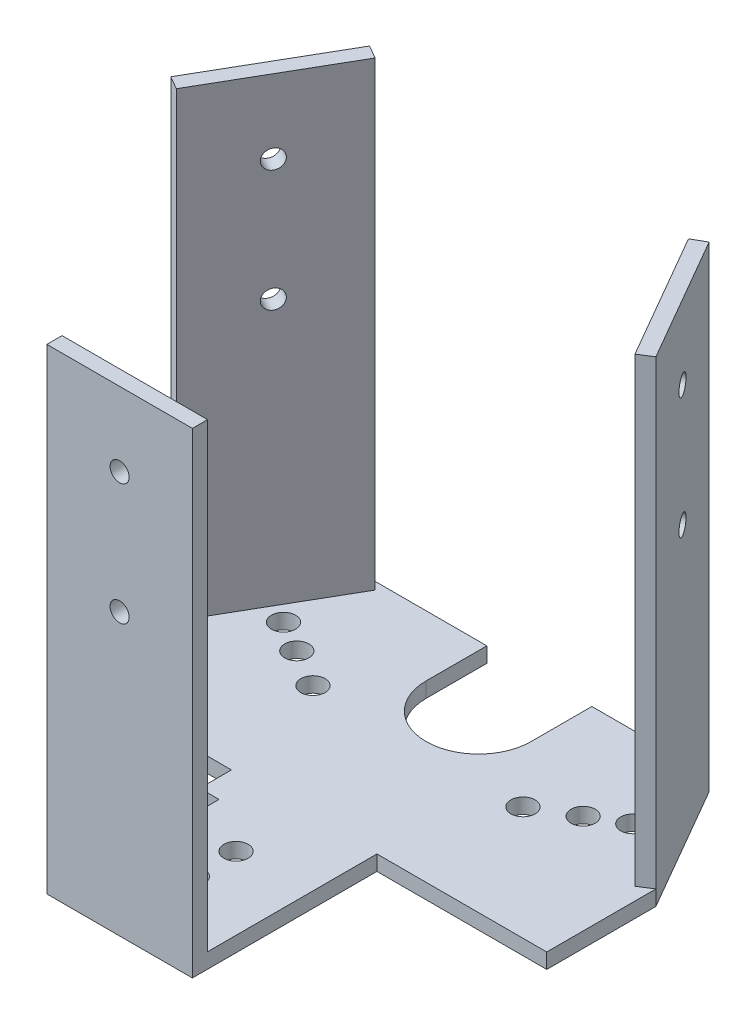
SolidWorks part; units mm, degrees
ref_plane "Front Plane" through (0, 0, 0) normal (0, 0, 1) x (1, 0, 0)
ref_plane "Top Plane" through (0, 0, 0) normal (0, 1, 0) x (1, 0, 0)
ref_plane "Right Plane" through (0, 0, 0) normal (1, 0, 0) x (0, 0, -1)
sketch "Sketch1" plane through (0, 0, 0) normal (0, 1, 0) x (1, 0, 0)
  line L0 (0, 11.43) -> (7.62, 24.6282)
  line L1 (0, 0) -> (50.8, 0)
  line L2 (0, 0) -> (0, 11.43)
  line L3 (0, 11.43) -> (50.8, 11.43)
  line L4 (50.8, 0) -> (50.8, 11.43)
  line L5 (50.8, 11.43) -> (43.18, 24.6282)
  line L6 (7.62, 24.6282) -> (43.18, 24.6282)
  line L7 (3.81, 18.0291) -> (44.3832, -5.3958) construction
  line L8 (17.78, 0) -> (33.02, 0)
  line L9 (17.78, 0) -> (17.78, -19.3279)
  line L10 (17.78, -19.3279) -> (33.02, -19.3279)
  line L11 (33.02, 0) -> (33.02, -19.3279)
  line L12 (46.99, 18.0291) -> (8.5613, -4.1577) construction
  line L13 (25.4, -19.3279) -> (25.4, 20.0669) construction
  line L15 (19.9, 18.2641) -> (30.9, 18.2641)
  line L16 (19.9, 18.2641) -> (19.9, 24.6282)
  line L17 (19.9, 24.6282) -> (30.9, 24.6282)
  line L18 (30.9, 18.2641) -> (30.9, 24.6282)
  circle A0 centre (43.6904, 16.1241) radius 1.27
  circle A1 centre (40.3909, 14.2191) radius 1.27
  circle A2 centre (36.3985, 11.9141) radius 1.27
  circle A3 centre (7.1096, 16.1241) radius 1.27
  circle A4 centre (10.4091, 14.2191) radius 1.27
  circle A5 centre (14.4015, 11.9141) radius 1.27
  circle A6 centre (25.4, -15.5179) radius 1.27
  circle A7 centre (25.4, -11.7079) radius 1.27
  circle A8 centre (25.4, -7.1359) radius 1.27
  circle A9 centre (25.4, 18.2641) radius 5.5
  point P23 (25.4, 5.5641)
  dimension "D11" = 3.81
  dimension "D12" = 3.81
  dimension "D13" = 2.54
  dimension "D14" = 2.54
  dimension "D15" = 2.54
  dimension "D16" = 12.7
  dimension "D17" = 3.81
  dimension "D18" = 3.81
  dimension "D19" = 2.54
  dimension "D20" = 2.54
  dimension "D21" = 2.54
  dimension "D22" = 3.81
  dimension "D23" = 3.81
  dimension "D24" = 12.7
  dimension "D25" = 2.54
  dimension "D26" = 2.54
  dimension "D27" = 2.54
  dimension "D28" = 12.7
  dimension "D29" = 11
  dimension "D1" = 50.8
  dimension "D2" = 11.43
  dimension "D3" = 30
  dimension "D4" = 15.24
  dimension "D5" = 30
  dimension "D6" = 15.24
  dimension "D7" = 15.24
  dimension "D8" = 24.892
  dimension "D9" = 17.78
  dimension "D10" = 12.7
extrude "Boss-Extrude2" add sketch "Sketch1" along normal blind 1.5875 contours A5 L3 L2 L1 L4 A2 | A5 L3 A2 L5 L6 L0 A4 A3 A1 A0 | L11 L1 L9 L10 A8 A7 A6
sketch "Sketch2" plane through (0, 1.5875, 0) normal (0, 1, 0) x (1, 0, 0)
  line L0 (17.78, 0) -> (17.78, -19.3279) construction
  line L1 (33.02, -19.3279) -> (17.78, -19.3279)
  line L2 (33.02, -19.3279) -> (33.02, -17.7404)
  line L3 (33.02, -17.7404) -> (17.78, -17.7404)
  line L4 (17.78, -19.3279) -> (17.78, -17.7404)
  line L5 (0, 11.43) -> (7.62, 24.6282)
  line L6 (7.62, 24.6282) -> (8.9948, 23.8345)
  line L7 (8.9948, 23.8345) -> (1.3748, 10.6362)
  line L8 (1.3748, 10.6362) -> (0, 11.43)
  line L9 (50.8, 11.43) -> (43.18, 24.6282)
  line L10 (50.8, 11.43) -> (43.18, 24.6282) construction
  line L11 (43.18, 24.6282) -> (41.8064, 23.8352)
  line L12 (41.8064, 23.8352) -> (49.46, 10.5787)
  line L13 (49.46, 10.5787) -> (50.8, 11.43)
  dimension "D1" = 1.5875
  dimension "D2" = 1.5875
  dimension "D3" = 1.5875
extrude "Boss-Extrude3" add sketch "Sketch2" along normal blind 48.26
sketch "Sketch3" plane through (0, 0, 19.3279) normal (0, 0, 1) x (1, 0, 0)
  line L0 (17.78, 49.8475) -> (33.02, 49.8475) construction
  line L1 (33.02, 49.8475) -> (33.02, 0) construction
  circle A0 centre (25.4, 42.1025) radius 1
  circle A1 centre (25.4, 29.4025) radius 1
  dimension "D1" = 2
  dimension "D2" = 7.745
  dimension "D3" = 7.62
  dimension "D4" = 2
  dimension "D5" = 12.7
extrude "Cut-Extrude1" cut sketch "Sketch3" against normal blind 2.54
sketch "Sketch4" plane through (43.0493, 0, -24.8545) normal (0.866, 0, -0.5) x (-0.5, 0, -0.866)
  line L0 (-15.5013, 49.8475) -> (-15.5013, 1.5875) construction
  line L1 (-15.5013, 49.8475) -> (-0.2613, 49.8475) construction
  circle A0 centre (-7.8813, 42.1025) radius 1
  circle A1 centre (-7.8813, 29.4025) radius 1
  dimension "D1" = 7.62
  dimension "D2" = 7.745
  dimension "D3" = 2
  dimension "D4" = 2
  dimension "D5" = 12.7
extrude "Cut-Extrude2" cut sketch "Sketch4" against normal blind 2.54
sketch "Sketch5" plane through (-4.9493, 0, -2.8575) normal (-0.866, 0, -0.5) x (-0.5, 0, 0.866)
  line L0 (-25.1387, 49.8475) -> (-9.8987, 49.8475) construction
  circle A0 centre (-17.3344, 42.1047) radius 1
  circle A1 centre (-17.3344, 29.4047) radius 1
  point P4 (-17.5187, 49.8475)
  dimension "D1" = 2
  dimension "D2" = 7.745
  dimension "D3" = 2
  dimension "D4" = 12.7
extrude "Cut-Extrude3" cut sketch "Sketch5" against normal blind 2.54
sketch "Sketch6" plane through (0, 0, 0) normal (0, -1, 0) x (-1, 0, 0)
  line L0 (-17.78, 0) -> (-17.78, -19.3279) construction
  line L1 (-17.78, -10.6919) -> (-19.812, -10.6919)
  line L2 (-17.78, -10.6919) -> (-17.78, -3.3259)
  line L3 (-17.78, -3.3259) -> (-19.812, -3.3259)
  line L4 (-19.812, -10.6919) -> (-19.812, -3.3259)
  line L5 (-17.78, -19.3279) -> (-33.02, -19.3279) construction
  dimension "D1" = 8.636
  dimension "D2" = 16.002
  dimension "D3" = 2.032
extrude "Cut-Extrude4" cut sketch "Sketch6" against normal blind 2.54
